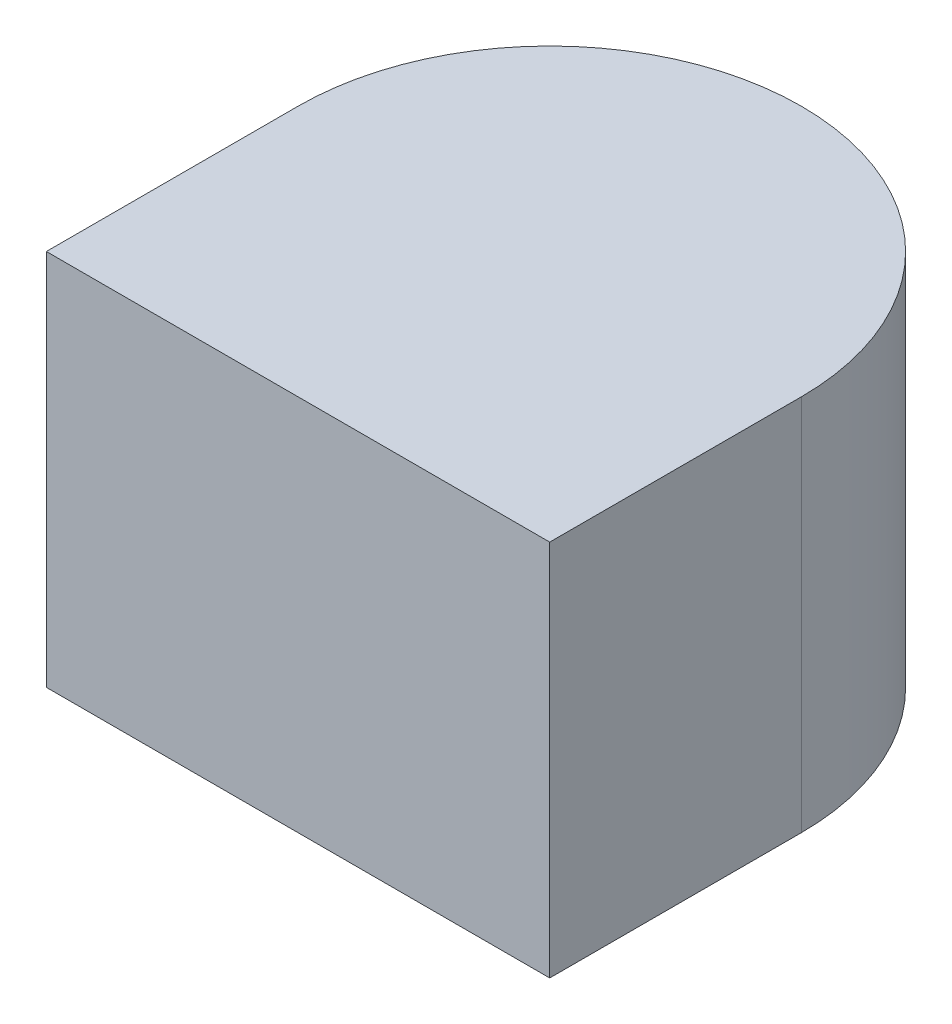
SolidWorks part; units mm, degrees
ref_plane "Přední rovina" through (0, 0, 0) normal (0, 0, 1) x (1, 0, 0)
ref_plane "Horní rovina" through (0, 0, 0) normal (0, 1, 0) x (1, 0, 0)
ref_plane "Pravá rovina" through (0, 0, 0) normal (1, 0, 0) x (0, 0, -1)
sketch "Sketch1" plane through (0, 0, 0) normal (0, 1, 0) x (1, 0, 0)
  line L0 (0, 0) -> (0, -20)
  line L1 (-10, -20) -> (10, -20)
  line L4 (10, -20) -> (10, -10)
  line L5 (-10, -20) -> (-10, -10)
  arc A0 (-10, -10) -> (10, -10) centre (0, -10) cw
  dimension "D2" = 10
  dimension "D1" = 10
extrude "Boss-Extrude1" add sketch "Sketch1" along normal blind 15 contours A0 L0 L1 L4 | A0 L5 L1 L0
